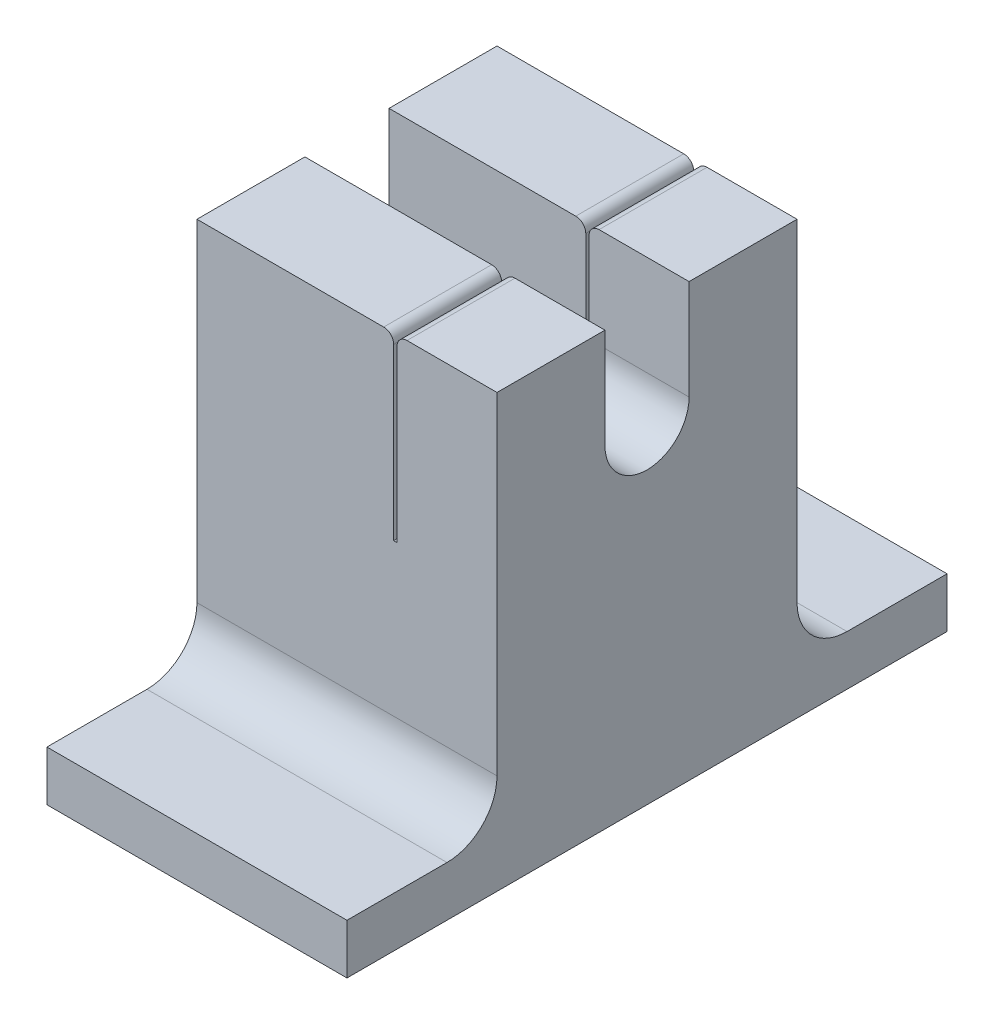
SolidWorks part; units mm, degrees
ref_plane "Front Plane" through (0, 0, 0) normal (0, 0, 1) x (1, 0, 0)
ref_plane "Top Plane" through (0, 0, 0) normal (0, 1, 0) x (1, 0, 0)
ref_plane "Right Plane" through (0, 0, 0) normal (1, 0, 0) x (0, 0, -1)
sketch "Sketch1" plane through (0, 0, 0) normal (0, 1, 0) x (1, 0, 0)
  line L1 (-15, -15) -> (15, -15)
  line L2 (-15, -15) -> (-15, 15)
  line L3 (-15, 15) -> (15, 15)
  line L4 (15, -15) -> (15, 15)
  point P5 (0, -15)
  point P9 (15, 0)
  dimension "D1" = 30
  dimension "D2" = 30
extrude "Boss-Extrude1" add sketch "Sketch1" along normal blind 33.2
sketch "Sketch2" plane through (-15, 0, 0) normal (-1, 0, 0) x (0, 0, 1)
  line L0 (-15, 33.2) -> (15, 33.2) construction
  circle A0 centre (0, 33.2) radius 4.205
  dimension "D1" = 8.41
extrude "Cut-Extrude1" cut sketch "Sketch2" against normal through all
sketch "Sketch4" plane through (15, 0, 0) normal (1, 0, 0) x (0, 0, -1)
  line L0 (-15, 0) -> (15, 0) construction
  line L1 (-30, 0) -> (30, 0)
  line L2 (-30, 0) -> (-30, 5)
  line L3 (-30, 5) -> (30, 5)
  line L4 (30, 0) -> (30, 5)
  point P4 (0, 0)
  dimension "D1" = 60
  dimension "D2" = 5
extrude "Boss-Extrude2" add sketch "Sketch4" against normal up to surface (30 mm away) up to face at (-15, 21.4325, 0)
fillet "Fillet1" radius 5 2 edges at (0, 5, -15) (0, 5, 15)
sketch "Sketch5" plane through (0, 33.2, 0) normal (0, 1, 0) x (1, 0, 0)
  line L4 (-15, 15) -> (-15, 4.205)
  line L5 (-15, 4.205) -> (15, 4.205)
  line L6 (15, 4.205) -> (15, 15)
  line L7 (15, 15) -> (-15, 15)
  line L8 (-15, 15) -> (-15, 4.205)
  line L9 (-15, 4.205) -> (15, 4.205)
  line L10 (15, 4.205) -> (15, 15)
  line L11 (15, 15) -> (-15, 15)
  line L12 (15, -15) -> (15, -4.205)
  line L13 (15, -4.205) -> (-15, -4.205)
  line L14 (-15, -4.205) -> (-15, -15)
  line L15 (-15, -15) -> (15, -15)
  line L16 (15, -15) -> (15, -4.205)
  line L17 (15, -4.205) -> (-15, -4.205)
  line L18 (-15, -4.205) -> (-15, -15)
  line L19 (-15, -15) -> (15, -15)
  dimension "D1" = 0
  dimension "D2" = 0
extrude "Boss-Extrude3" add sketch "Sketch5" along normal blind 10
sketch "Sketch6" plane through (0, 43.2, 0) normal (0, 1, 0) x (1, 0, 0)
  line L0 (-15, -15) -> (15, -15) construction
  line L1 (4.67, 15) -> (5, 15)
  line L2 (4.67, 15) -> (4.67, -15)
  line L3 (4.67, -15) -> (5, -15)
  line L4 (5, 15) -> (5, -15)
  line L5 (4.67, 15) -> (5, -15) construction
  line L6 (4.67, -15) -> (5, 15) construction
  line L7 (15, -4.205) -> (15, 4.205) construction
  line L8 (15, 15) -> (-15, 15) construction
  point P0 (4.835, 0)
  point P8 (10.5673, 0.4814)
  point P11 (0, 0)
  point P12 (5, 15)
  dimension "D1" = 0.33
  dimension "D2" = 10
extrude "Cut-Extrude2" cut sketch "Sketch6" against normal blind 18
fillet "Fillet2" radius 1 4 edges at (4.67, 43.2, 9.6025) (5, 43.2, 9.6025) (5, 43.2, -9.6025) (4.67, 43.2, -9.6025)
